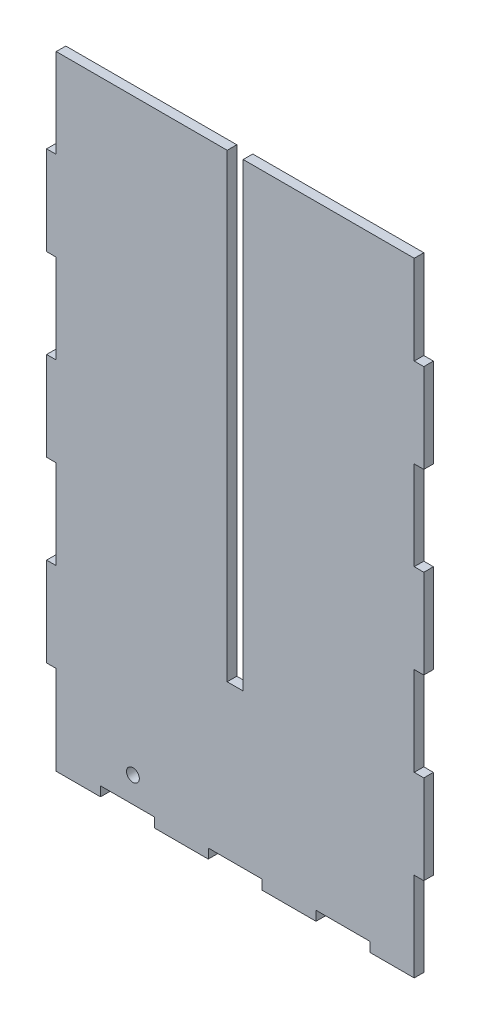
SolidWorks part; units mm, degrees
ref_plane "Front Plane" through (0, 0, 0) normal (0, 0, 1) x (1, 0, 0)
ref_plane "Top Plane" through (0, 0, 0) normal (0, 1, 0) x (1, 0, 0)
ref_plane "Right Plane" through (0, 0, 0) normal (1, 0, 0) x (0, 0, -1)
sketch "Sketch2" plane through (0, 0, 0) normal (0, 0, 1) x (1, 0, 0)
  line L0 (0, 152.4) -> (0, -152.4) construction
  line L1 (-88.9, 152.4) -> (88.9, 152.4)
  line L2 (-88.9, 152.4) -> (-88.9, -152.4)
  line L3 (-88.9, -152.4) -> (88.9, -152.4)
  line L4 (88.9, 152.4) -> (88.9, -152.4)
  line L5 (-88.9, 108.1768) -> (-88.9, 63.9536)
  line L6 (-88.9, 152.4) -> (-93.6625, 152.4)
  line L7 (-88.9, 152.4) -> (-88.9, 108.1768)
  line L8 (-88.9, 108.1768) -> (-93.6625, 108.1768)
  line L9 (-93.6625, 152.4) -> (-93.6625, 108.1768)
  line L10 (88.9, 152.4) -> (93.6625, 152.4)
  line L11 (88.9, 152.4) -> (88.9, 108.1768)
  line L12 (88.9, 108.1768) -> (93.6625, 108.1768)
  line L13 (93.6625, 152.4) -> (93.6625, 108.1768)
  line L14 (-66.9018, -152.4) -> (-93.6625, -152.4)
  line L15 (-66.9018, -152.4) -> (-66.9018, -157.1625)
  line L16 (-66.9018, -157.1625) -> (-93.6625, -157.1625)
  line L17 (-93.6625, -152.4) -> (-93.6625, -157.1625)
  line L18 (-88.9, 108.1768) -> (-93.6625, 108.1768)
  line L19 (-93.6625, 108.1768) -> (-93.6625, 63.9536)
  line L20 (-88.9, 63.9536) -> (-93.6625, 63.9536)
  line L21 (88.9, 108.1768) -> (88.9, 63.9536)
  line L22 (88.9, 108.1768) -> (93.6625, 108.1768)
  line L23 (93.6625, 108.1768) -> (93.6625, 63.9536)
  line L24 (88.9, 63.9536) -> (93.6625, 63.9536)
  line L25 (-88.9, 63.9536) -> (-88.9, 19.7304)
  line L26 (-88.9, 63.9536) -> (-93.6625, 63.9536)
  line L27 (-93.6625, 63.9536) -> (-93.6625, 19.7304)
  line L28 (-88.9, 19.7304) -> (-93.6625, 19.7304)
  line L29 (88.9, 63.9536) -> (88.9, 19.7304)
  line L30 (88.9, 63.9536) -> (93.6625, 63.9536)
  line L31 (93.6625, 63.9536) -> (93.6625, 19.7304)
  line L32 (88.9, 19.7304) -> (93.6625, 19.7304)
  line L33 (-88.9, 19.7304) -> (-88.9, -24.4929)
  line L34 (-88.9, 19.7304) -> (-93.6625, 19.7304)
  line L35 (-93.6625, 19.7304) -> (-93.6625, -24.4929)
  line L36 (-88.9, -24.4929) -> (-93.6625, -24.4929)
  line L37 (88.9, 19.7304) -> (88.9, -24.4929)
  line L38 (88.9, 19.7304) -> (93.6625, 19.7304)
  line L39 (93.6625, 19.7304) -> (93.6625, -24.4929)
  line L40 (88.9, -24.4929) -> (93.6625, -24.4929)
  line L41 (-88.9, -24.4929) -> (-88.9, -68.7161)
  line L42 (-88.9, -24.4929) -> (-93.6625, -24.4929)
  line L43 (-93.6625, -24.4929) -> (-93.6625, -68.7161)
  line L44 (-88.9, -68.7161) -> (-93.6625, -68.7161)
  line L45 (88.9, -24.4929) -> (88.9, -68.7161)
  line L46 (88.9, -24.4929) -> (93.6625, -24.4929)
  line L47 (93.6625, -24.4929) -> (93.6625, -68.7161)
  line L48 (88.9, -68.7161) -> (93.6625, -68.7161)
  line L49 (-88.9, -68.7161) -> (-88.9, -112.9393)
  line L50 (-88.9, -68.7161) -> (-93.6625, -68.7161)
  line L51 (-93.6625, -68.7161) -> (-93.6625, -112.9393)
  line L52 (-88.9, -112.9393) -> (-93.6625, -112.9393)
  line L53 (88.9, -68.7161) -> (88.9, -112.9393)
  line L54 (88.9, -68.7161) -> (93.6625, -68.7161)
  line L55 (93.6625, -68.7161) -> (93.6625, -112.9393)
  line L56 (88.9, -112.9393) -> (93.6625, -112.9393)
  line L57 (-88.9, -112.9393) -> (-88.9, -157.1625)
  line L58 (-88.9, -112.9393) -> (-93.6625, -112.9393)
  line L59 (-93.6625, -112.9393) -> (-93.6625, -157.1625)
  line L60 (-88.9, -157.1625) -> (-93.6625, -157.1625)
  line L61 (88.9, -112.9393) -> (88.9, -157.1625)
  line L62 (88.9, -112.9393) -> (93.6625, -112.9393)
  line L63 (93.6625, -112.9393) -> (93.6625, -157.1625)
  line L64 (88.9, -157.1625) -> (93.6625, -157.1625)
  line L65 (-40.1411, -152.4) -> (-40.1411, -157.1625)
  line L66 (-40.1411, -152.4) -> (-66.9018, -152.4)
  line L67 (-66.9018, -152.4) -> (-66.9018, -157.1625)
  line L68 (-40.1411, -157.1625) -> (-66.9018, -157.1625)
  line L69 (-13.3804, -152.4) -> (-13.3804, -157.1625)
  line L70 (-13.3804, -152.4) -> (-40.1411, -152.4)
  line L71 (-40.1411, -152.4) -> (-40.1411, -157.1625)
  line L72 (-13.3804, -157.1625) -> (-40.1411, -157.1625)
  line L73 (13.3804, -152.4) -> (13.3804, -157.1625)
  line L74 (13.3804, -152.4) -> (-13.3804, -152.4)
  line L75 (-13.3804, -152.4) -> (-13.3804, -157.1625)
  line L76 (13.3804, -157.1625) -> (-13.3804, -157.1625)
  line L77 (40.1411, -152.4) -> (40.1411, -157.1625)
  line L78 (40.1411, -152.4) -> (13.3804, -152.4)
  line L79 (13.3804, -152.4) -> (13.3804, -157.1625)
  line L80 (40.1411, -157.1625) -> (13.3804, -157.1625)
  line L81 (66.9018, -152.4) -> (66.9018, -157.1625)
  line L82 (66.9018, -152.4) -> (40.1411, -152.4)
  line L83 (40.1411, -152.4) -> (40.1411, -157.1625)
  line L84 (66.9018, -157.1625) -> (40.1411, -157.1625)
  line L85 (93.6625, -152.4) -> (93.6625, -157.1625)
  line L86 (93.6625, -152.4) -> (66.9018, -152.4)
  line L87 (66.9018, -152.4) -> (66.9018, -157.1625)
  line L88 (93.6625, -157.1625) -> (66.9018, -157.1625)
  point P6 (0, 0)
  dimension "D1" = 177.8
  dimension "D2" = 187.325
  dimension "D3" = 304.8
  dimension "D4" = 309.5625
  dimension "D6" = 44.2232
  dimension "D8" = 26.7607
  dimension "D5" = 7
  dimension "D7" = 7
extrude "Boss-Extrude1" add sketch "Sketch2" along normal blind 4.7625 contours L0 L1 L2 L3 | L1 L0 L3 L4 | L20 L2 L8 L19 | L36 L2 L28 L35 | L52 L2 L44 L51 | L3 L57 L16 L15 | L72 L69 L3 L65 | L80 L77 L3 L73 | L4 L56 L55 L48 | L4 L40 L39 L32 | L4 L24 L23 L12 | L88 L61 L3 L81
sketch "Sketch3" plane through (0, 0, 4.7625) normal (0, 0, 1) x (1, 0, 0)
  line L0 (-88.9, 152.4) -> (88.9, 152.4) construction
  line L1 (-3.9688, 152.4) -> (3.9687, 152.4)
  line L2 (-3.9688, 152.4) -> (-3.9687, -76.2)
  line L3 (-3.9687, -76.2) -> (3.9688, -76.2)
  line L4 (3.9687, 152.4) -> (3.9688, -76.2)
  line L5 (0, -76.2) -> (0, 0) construction
  dimension "D1" = 7.9375
  dimension "D2" = 228.6
extrude "Cut-Extrude1" cut sketch "Sketch3" against normal through all
sketch "Sketch4" plane through (0, 0, 4.7625) normal (0, 0, 1) x (1, 0, 0)
  line L0 (-66.9018, -152.4) -> (-40.1411, -152.4) construction
  line L1 (-88.9, -112.9393) -> (-88.9, -157.1625) construction
  circle A0 centre (-50.8, -139.7) radius 3.175
  dimension "D1" = 6.35
  dimension "D2" = 12.7
  dimension "D3" = 38.1
extrude "Cut-Extrude2" cut sketch "Sketch4" against normal through all
equation "\"Height\"= 12in"
equation "\"Depth\"= 7in"
equation "\"WallThickness\"= 0.1875in"
equation "\"FloorThickness\"= 0.1875in"
equation "\"D1@Sketch2\"=\"Depth\""
equation "\"D2@Sketch2\"=\"D1@Sketch2\"+2*\"WallThickness\""
equation "\"D3@Sketch2\"=\"Height\""
equation "\"D4@Sketch2\"=\"D3@Sketch2\"+\"WallThickness\""
equation "\"D6@Sketch2\"=\"D4@Sketch2\"/\"D5@Sketch2\""
equation "\"D8@Sketch2\"=\"D2@Sketch2\"/\"D7@Sketch2\""
equation "\"D1@Boss-Extrude1\"=\"WallThickness\""
equation "\"Width\" = 30in"
